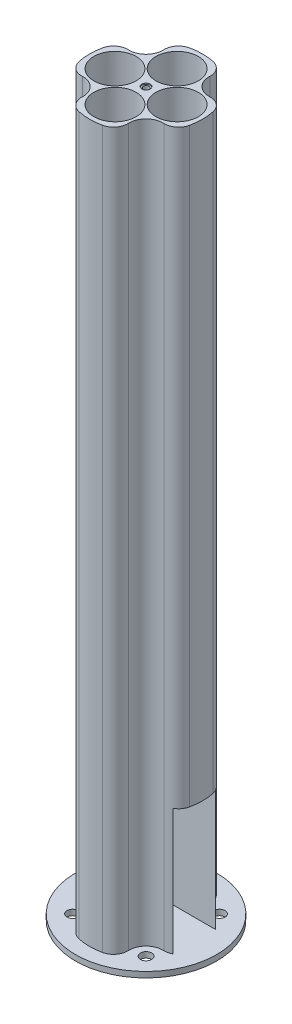
SolidWorks part; units mm, degrees
ref_plane "Front Plane" through (0, 0, 0) normal (0, 0, 1) x (1, 0, 0)
ref_plane "Top Plane" through (0, 0, 0) normal (0, 1, 0) x (1, 0, 0)
ref_plane "Right Plane" through (0, 0, 0) normal (1, 0, 0) x (0, 0, -1)
sketch "Sketch1" plane through (0, 0, 0) normal (0, 1, 0) x (1, 0, 0)
  circle A0 centre (0, 0) radius 100
  dimension "D1" = 200
extrude "Boss-Extrude2" add sketch "Sketch1" along normal blind 1120 contours A0
sketch "Sketch4" plane through (0, 1120, 0) normal (0, 1, 0) x (1, 0, 0)
  line L0 (0, 0) -> (0, -55) construction
  line L1 (0, 0) -> (55, 0) construction
  line L2 (0, 0) -> (0, 55) construction
  line L3 (0, 0) -> (-55, 0) construction
  circle A0 centre (55, 0) radius 37.5
  circle A1 centre (0, 55) radius 37.5
  circle A2 centre (-55, 0) radius 37.5
  circle A3 centre (0, -55) radius 37.5
  dimension "D2" = 75
  dimension "D1" = 55
extrude "Cut-Extrude1" cut sketch "Sketch4" against normal blind 1100 contours A1 | A2 | A0 | A3
sketch "Sketch6" plane through (0, 1120, 0) normal (0, 1, 0) x (1, 0, 0)
  line L0 (0, 0) -> (-70.7107, 70.7107) construction
  circle A0 centre (0, 0) radius 15
  circle A1 centre (-70.7107, 70.7107) radius 30.03
  circle A2 centre (0, 0) radius 100
  circle A3 centre (0, 0) radius 100
  circle A4 centre (0, 0) radius 15
  circle A5 centre (70.7107, 70.7107) radius 30.03
  circle A6 centre (0, 0) radius 15
  circle A7 centre (70.7107, -70.7107) radius 30.03
  circle A8 centre (0, 0) radius 15
  circle A9 centre (-70.7107, -70.7107) radius 30.03
  point P20 (0, 0)
  circle M8 centre (0, 0) radius 100
  dimension "D1" = 30
  dimension "D2" = 0
  dimension "D3" = 4
extrude "Cut-Extrude2" cut sketch "Sketch6" against normal through all contours L0 A1 M8 | A1 L0 A3 | A3 A5 | A3 A7 | A3 A9
sketch "Sketch7" plane through (0, 1120, 0) normal (0, 1, 0) x (1, 0, 0)
  circle A0 centre (0, 0) radius 5
  dimension "D1" = 10
extrude "Cut-Extrude3" cut sketch "Sketch7" against normal blind 1200
fillet "Fillet1" radius 25 8 edges at (-88.516, 560, 46.5286) (-46.5286, 560, 88.516) (-46.5286, 560, -88.516) (-88.516, 560, -46.5286) (88.516, 560, -46.5286) (46.5286, 560, -88.516) (46.5286, 560, 88.516) (88.516, 560, 46.5286)
sketch "Sketch8" plane through (0, 1120, 0) normal (0, 1, 0) x (1, 0, 0)
  line L1 (147.8756, 155.206) -> (-128.3047, 155.206)
  line L2 (147.8756, 155.206) -> (147.8756, -161.0426)
  line L3 (147.8756, -161.0426) -> (-128.3047, -161.0426)
  line L4 (-128.3047, 155.206) -> (-128.3047, -161.0426)
extrude "Cut-Extrude4" cut sketch "Sketch8" against normal blind 65
sketch "Sketch9" plane through (0, 1055, 0) normal (0, 1, 0) x (1, 0, 0)
  circle A0 centre (0, 0) radius 7.5
  dimension "D1" = 15
extrude "Cut-Extrude5" cut sketch "Sketch9" against normal blind 2
sketch "Sketch10" plane through (0, 0, 0) normal (0, -1, 0) x (1, 0, 0)
  arc A16 (20.9906, 97.7722) -> (-20.9906, 97.7722) centre (0, 0) ccw
  arc A17 (-20.9906, 97.7722) -> (-40.7146, 72.1396) centre (-15.743, 73.3291) ccw
  arc A18 (-72.1396, 40.7146) -> (-40.7146, 72.1396) centre (-70.7107, 70.7107) ccw
  arc A19 (-72.1396, 40.7146) -> (-97.7722, 20.9906) centre (-73.3291, 15.743) ccw
  arc A20 (-97.7722, 20.9906) -> (-97.7722, -20.9906) centre (0, 0) ccw
  arc A21 (-97.7722, -20.9906) -> (-72.1396, -40.7146) centre (-73.3291, -15.743) ccw
  arc A22 (-40.7146, -72.1396) -> (-72.1396, -40.7146) centre (-70.7107, -70.7107) ccw
  arc A23 (-40.7146, -72.1396) -> (-20.9906, -97.7722) centre (-15.743, -73.3291) ccw
  arc A24 (-20.9906, -97.7722) -> (20.9906, -97.7722) centre (0, 0) ccw
  arc A25 (20.9906, -97.7722) -> (40.7146, -72.1396) centre (15.743, -73.3291) ccw
  arc A26 (72.1396, -40.7146) -> (40.7146, -72.1396) centre (70.7107, -70.7107) ccw
  arc A27 (72.1396, -40.7146) -> (97.7722, -20.9906) centre (73.3291, -15.743) ccw
  arc A28 (97.7722, -20.9906) -> (97.7722, 20.9906) centre (0, 0) ccw
  arc A29 (97.7722, 20.9906) -> (72.1396, 40.7146) centre (73.3291, 15.743) ccw
  arc A30 (40.7146, 72.1396) -> (72.1396, 40.7146) centre (70.7107, 70.7107) ccw
  arc A31 (40.7146, 72.1396) -> (20.9906, 97.7722) centre (15.743, 73.3291) ccw
  arc A32 (20.9906, 97.7722) -> (-20.9906, 97.7722) centre (0, 0) ccw
  arc A33 (-20.9906, 97.7722) -> (-40.7146, 72.1396) centre (-15.743, 73.3291) ccw
  arc A34 (-72.1396, 40.7146) -> (-40.7146, 72.1396) centre (-70.7107, 70.7107) ccw
  arc A35 (-72.1396, 40.7146) -> (-97.7722, 20.9906) centre (-73.3291, 15.743) ccw
  arc A36 (-97.7722, 20.9906) -> (-97.7722, -20.9906) centre (0, 0) ccw
  arc A37 (-97.7722, -20.9906) -> (-72.1396, -40.7146) centre (-73.3291, -15.743) ccw
  arc A38 (-40.7146, -72.1396) -> (-72.1396, -40.7146) centre (-70.7107, -70.7107) ccw
  arc A39 (-40.7146, -72.1396) -> (-20.9906, -97.7722) centre (-15.743, -73.3291) ccw
  arc A40 (-20.9906, -97.7722) -> (20.9906, -97.7722) centre (0, 0) ccw
  arc A41 (20.9906, -97.7722) -> (40.7146, -72.1396) centre (15.743, -73.3291) ccw
  arc A42 (72.1396, -40.7146) -> (40.7146, -72.1396) centre (70.7107, -70.7107) ccw
  arc A43 (72.1396, -40.7146) -> (97.7722, -20.9906) centre (73.3291, -15.743) ccw
  arc A44 (97.7722, -20.9906) -> (97.7722, 20.9906) centre (0, 0) ccw
  arc A45 (97.7722, 20.9906) -> (72.1396, 40.7146) centre (73.3291, 15.743) ccw
  arc A46 (40.7146, 72.1396) -> (72.1396, 40.7146) centre (70.7107, 70.7107) ccw
  arc A47 (40.7146, 72.1396) -> (20.9906, 97.7722) centre (15.743, 73.3291) ccw
  dimension "D1" = 0
extrude "Boss-Extrude3" add sketch "Sketch10" along normal blind 223.2146
sketch "Sketch11" plane through (0, -223.2146, 0) normal (0, -1, 0) x (1, 0, 0)
  circle A0 centre (0, 0) radius 125
  dimension "D1" = 250
extrude "Boss-Extrude4" add sketch "Sketch11" against normal blind 10
sketch "Sketch12" plane through (0, 0, 0) normal (1, 0, 0) x (0, 0, -1)
  line L0 (37.5, 20) -> (-37.5, 20) construction
  line L1 (37.5, 20) -> (-37.5, 20)
  line L2 (-37.5, 20) -> (-37.5, -213.2146)
  line L3 (-20.9906, -213.2146) -> (-40.743, -213.2146) construction
  line L4 (37.5, 20) -> (37.5, -213.2146)
  line L5 (40.743, -213.2146) -> (20.9906, -213.2146) construction
  line L6 (-37.5, 10) -> (37.5, 10)
  line L7 (-37.5, -213.2146) -> (37.5, -213.2146)
  dimension "D1" = 10
extrude "Cut-Extrude6" cut sketch "Sketch12" against normal mid plane 246 contours L2 L7 L4 L6
sketch "Sketch13" plane through (0, -223.2146, 0) normal (0, -1, 0) x (1, 0, 0)
  line L0 (0, 0) -> (125, 0) construction
  line L1 (0, 0) -> (88.3883, 88.3883) construction
  circle A0 centre (0, 0) radius 125
  circle A1 centre (65, 65) radius 10
  circle A2 centre (65, -65) radius 10
  circle A3 centre (-65, -65) radius 10
  circle A4 centre (-65, 65) radius 10
  point P7 (0, 0)
  point P8 (-67.2086, 67.2086)
  point P16 (0, 0)
  dimension "D2" = 20
  dimension "D4" = 130
  dimension "D1" = 45
  dimension "D3" = 4
extrude "Cut-Extrude7" cut sketch "Sketch13" against normal up to next contours A4 | A1 | A2 | A3
